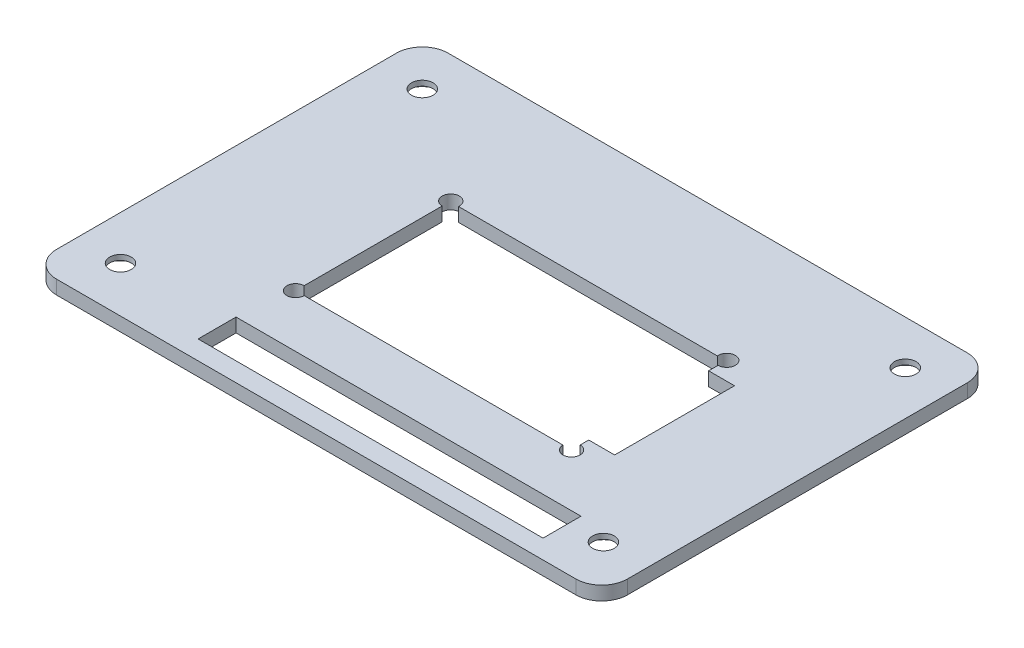
SolidWorks part; units mm, degrees
ref_plane "前视基准面" through (0, 0, 0) normal (0, 0, 1) x (1, 0, 0)
ref_plane "上视基准面" through (0, 0, 0) normal (0, 1, 0) x (1, 0, 0)
ref_plane "右视基准面" through (0, 0, 0) normal (1, 0, 0) x (0, 0, -1)
sketch "草图1" plane through (0, 0, 0) normal (0, 1, 0) x (1, 0, 0)
  line L1 (-30.1, -22.7) -> (30.1, -22.7)
  line L2 (-33.1, -19.7) -> (-33.1, 19.7)
  line L3 (-30.1, 22.7) -> (30.1, 22.7)
  line L4 (33.1, -19.7) -> (33.1, 19.7)
  line L5 (-33.1, -22.7) -> (33.1, 22.7) construction
  line L6 (-33.1, 22.7) -> (33.1, -22.7) construction
  arc A0 (30.1, 22.7) -> (33.1, 19.7) centre (30.1, 19.7) cw
  arc A1 (-33.1, 19.7) -> (-30.1, 22.7) centre (-30.1, 19.7) cw
  arc A2 (30.1, -22.7) -> (33.1, -19.7) centre (30.1, -19.7) ccw
  arc A3 (-30.1, -22.7) -> (-33.1, -19.7) centre (-30.1, -19.7) cw
  point P0 (0, 0)
  dimension "D3" = 3
  dimension "D4" = 3
  dimension "D1" = 45.4
  dimension "D2" = 66.2
extrude "凸台-拉伸1" add sketch "草图1" along normal blind 1.6
sketch "草图5" plane through (0, 0, 0) normal (0, -1, 0) x (1, 0, 0)
  line L0 (-33.1, -19.7) -> (-33.1, 19.7) construction
  line L1 (30.1, -22.7) -> (-30.1, -22.7) construction
  circle A0 centre (-28, -17.6) radius 2.6
  circle A1 centre (28, -17.6) radius 2.6
  circle A2 centre (28, 17.4) radius 2.6
  circle A3 centre (-28, 17.4) radius 2.6
  point P0 (-28, -17.6)
  point P10 (28, -17.6)
  point P13 (28, 17.4)
  point P16 (-28, 17.4)
  dimension "D3" = 5.2
  dimension "D1" = 5.1
  dimension "D2" = 5.1
  dimension "D4" = 2
  dimension "D5" = 2
extrude "正螺丝孔" cut sketch "草图5" against normal blind 1
sketch "草图7" plane through (0, 1, 0) normal (0, -1, 0) x (1, 0, 0)
  circle A0 centre (-28, -17.6) radius 1.25
  circle A1 centre (28, -17.6) radius 1.25
  circle A2 centre (28, 17.4) radius 1.25
  circle A3 centre (-28, 17.4) radius 1.25
  dimension "D1" = 2.5
  dimension "D2" = 2
  dimension "D3" = 2
extrude "背螺丝孔" cut sketch "草图7" against normal up to next
sketch "草图9" plane through (0, 0, 0) normal (0, -1, 0) x (-1, 0, 0)
  line L0 (-30.1, 22.7) -> (30.1, 22.7) construction
  line L5 (33.1, 19.7) -> (33.1, -19.7) construction
  line L6 (30.1, -22.7) -> (-30.1, -22.7) construction
  line L11 (15.9, -20.5) -> (-24.1, -20.5)
  line L12 (15.9, -20.5) -> (15.9, -16.1)
  line L13 (15.9, -16.1) -> (-24.1, -16.1)
  line L14 (-24.1, -20.5) -> (-24.1, -16.1)
  line L15 (-33.1, -19.7) -> (-33.1, 19.7) construction
  line L17 (-15.905, 1008) -> (-15.905, 7.9) construction
  line L18 (-16.9, -8) -> (-16.9, -9)
  line L19 (-15.905, 7.9) -> (14.105, 7.9)
  line L20 (-16.9, 7) -> (-16.9, 5.9)
  line L21 (-15.905, -10) -> (14.1, -10)
  line L22 (15.1, 7) -> (15.1, -9)
  line L23 (-16.9, -8) -> (-19.9, -8)
  line L25 (-16.9, 5.9) -> (-19.9, 5.9)
  line L26 (-19.9, -8) -> (-19.9, 5.9)
  line L27 (-15.905, -10) -> (-15.905, -1011) construction
  arc A0 (14.1, -10) -> (15.1, -9) centre (15.1, -10) ccw
  arc A1 (-16.9, -9) -> (-15.905, -10) centre (-16.905, -10) ccw
  arc A2 (15.1, 7) -> (14.105, 7.9) centre (15.1, 8) ccw
  arc A3 (-15.905, 7.9) -> (-16.9, 7) centre (-16.9, 8) ccw
  dimension "D8" = 2
  dimension "D6" = 2
  dimension "D2" = 32
  dimension "D3" = 18
  dimension "D4" = 14.8
  dimension "D5" = 18
  dimension "D7" = 3
  dimension "D9" = 40
  dimension "D10" = 4.4
  dimension "D11" = 2.2
  dimension "D12" = 9
  dimension "D13" = 2
extrude "切除-拉伸1" cut sketch "草图9" against normal up to next
